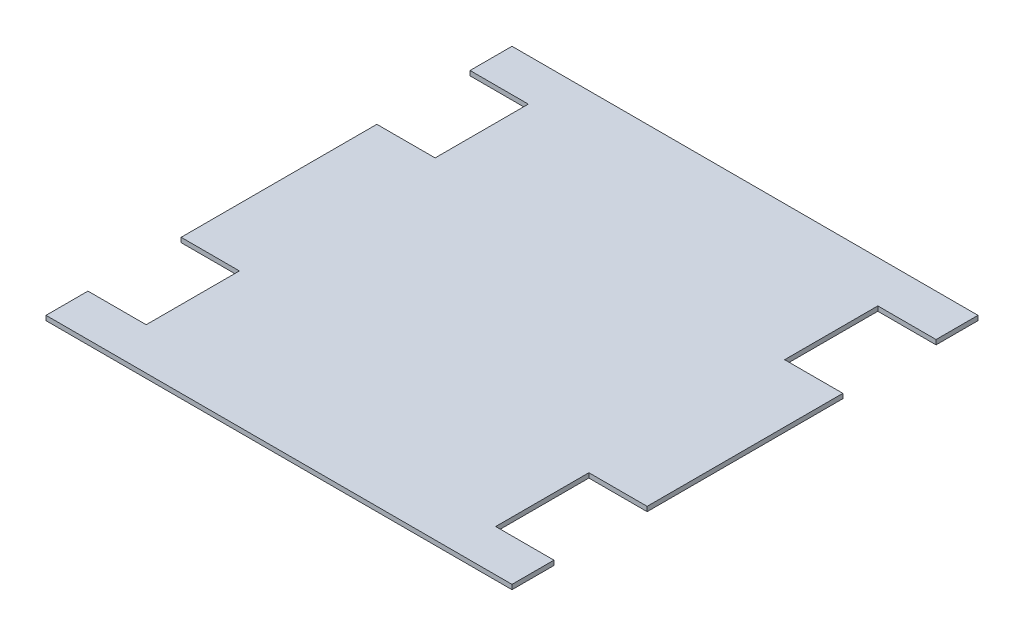
SolidWorks part; units mm, degrees
ref_plane "Front Plane" through (0, 0, 0) normal (0, 0, 1) x (1, 0, 0)
ref_plane "Top Plane" through (0, 0, 0) normal (0, 1, 0) x (1, 0, 0)
ref_plane "Right Plane" through (0, 0, 0) normal (1, 0, 0) x (0, 0, -1)
sketch "Sketch1" plane through (0, 0, 0) normal (0, 1, 0) x (1, 0, 0)
  line L1 (-250, 250) -> (250, 250)
  line L2 (-250, 250) -> (-250, -250)
  line L3 (-250, -250) -> (250, -250)
  line L4 (250, 250) -> (250, -250)
  line L5 (-250, 250) -> (250, -250) construction
  line L6 (-250, -250) -> (250, 250) construction
  point P0 (0, 0)
extrude "Boss-Extrude1" add sketch "Sketch1" along normal blind 5
sketch "Sketch3" plane through (0, 5, 0) normal (0, 1, 0) x (1, 0, 0)
  line L0 (-250, 250) -> (-250, 155)
  line L1 (-250, 250) -> (-250, -250) construction
  line L2 (-250, -250) -> (-250, -155)
  line L3 (250, 250) -> (250, 155)
  line L4 (-312.5, -105) -> (-187.5, -105)
  line L5 (-312.5, -105) -> (-312.5, -205)
  line L6 (-312.5, -205) -> (-187.5, -205)
  line L7 (-187.5, -105) -> (-187.5, -205)
  line L8 (-312.5, -105) -> (-187.5, -205) construction
  line L9 (-312.5, -205) -> (-187.5, -105) construction
  line L10 (-312.5, 205) -> (-187.5, 205)
  line L11 (-312.5, 205) -> (-312.5, 105)
  line L12 (-312.5, 105) -> (-187.5, 105)
  line L13 (-187.5, 205) -> (-187.5, 105)
  line L14 (-312.5, 205) -> (-187.5, 105) construction
  line L15 (-312.5, 105) -> (-187.5, 205) construction
  line L16 (250, -250) -> (250, 250) construction
  line L17 (250, -250) -> (250, -155)
  line L19 (187.5, 205) -> (312.5, 205)
  line L20 (187.5, 205) -> (187.5, 105)
  line L21 (187.5, 105) -> (312.5, 105)
  line L22 (312.5, 205) -> (312.5, 105)
  line L23 (187.5, 205) -> (312.5, 105) construction
  line L24 (187.5, 105) -> (312.5, 205) construction
  line L25 (187.5, -105) -> (312.5, -105)
  line L26 (187.5, -105) -> (187.5, -205)
  line L27 (187.5, -205) -> (312.5, -205)
  line L28 (312.5, -105) -> (312.5, -205)
  line L29 (187.5, -105) -> (312.5, -205) construction
  line L30 (187.5, -205) -> (312.5, -105) construction
  line M4 (250, -250) -> (250, 250)
  line M6 (-250, 250) -> (-250, -250)
extrude "Cut-Extrude1" cut sketch "Sketch3" against normal blind 5 contours L13 L10 L0 L12 M6 | L7 L4 L6 M6 | L26 L27 L17 L25 M4 | L20 L21 L19 M4
